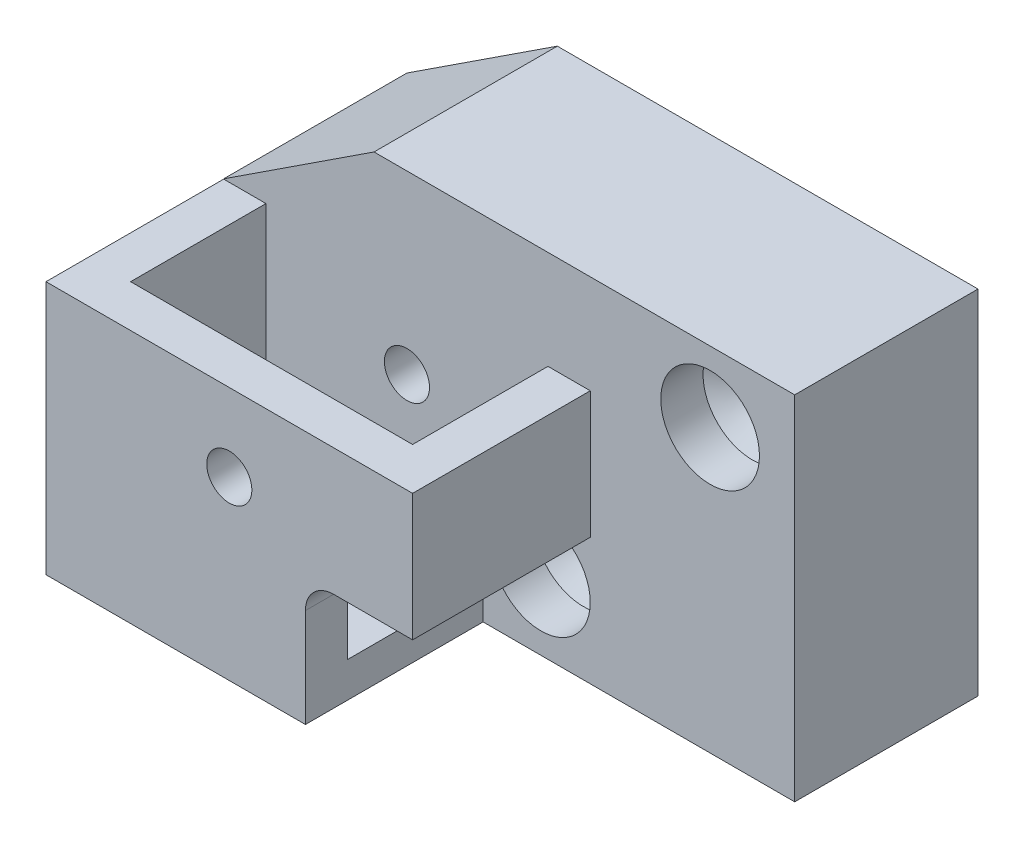
SolidWorks part; units mm, degrees
ref_plane "Спереди" through (0, 0, 0) normal (0, 0, 1) x (1, 0, 0)
ref_plane "Сверху" through (0, 0, 0) normal (0, 1, 0) x (1, 0, 0)
ref_plane "Справа" through (0, 0, 0) normal (1, 0, 0) x (0, 0, -1)
ref_plane "Плоскость4" through (272.1, 0, 0) normal (1, 0, 0) x (0, 0, -1)
sketch "Эскиз1" plane through (272.1, 0, 0) normal (1, 0, 0) x (0, 0, -1)
  line L0 (-23.1, 24) -> (-23.1, 15)
  line L1 (-23.1, 15) -> (-10.5, 15)
  line L2 (-10.5, 15) -> (-10.5, 24)
  line L3 (-10.5, 24) -> (-23.1, 24)
extrude "Бобышка-Вытянуть1" add sketch "Эскиз1" against normal blind 3
sketch "Эскиз2" plane through (269.1, 0, 0) normal (-1, 0, 0) x (0, 0, 1)
  line L0 (20.1, 15) -> (20.1, 24)
  line L1 (20.1, 24) -> (23.1, 24)
  line L2 (23.1, 24) -> (23.1, 15)
  line L3 (23.1, 15) -> (20.1, 15)
extrude "Бобышка-Вытянуть2" add sketch "Эскиз2" along normal blind 20
sketch "Эскиз3" plane through (249.1, 0, 0) normal (-1, 0, 0) x (0, 0, 1)
  line L0 (23.1, 15) -> (10.5, 15)
  line L1 (10.5, 15) -> (10.5, 24)
  line L2 (10.5, 24) -> (23.1, 24)
  line L3 (23.1, 24) -> (23.1, 15)
extrude "Бобышка-Вытянуть3" add sketch "Эскиз3" along normal blind 3
sketch "Эскиз4" plane through (0, 15, 0) normal (0, -1, 0) x (1, 0, 0)
  line L0 (264.5, 23.1) -> (264.5, 20.1)
  line L1 (264.5, 20.1) -> (249.1, 20.1)
  line L2 (249.1, 20.1) -> (249.1, 10.5)
  line L3 (249.1, 10.5) -> (246.1, 10.5)
  line L4 (246.1, 10.5) -> (246.1, 23.1)
  line L5 (246.1, 23.1) -> (264.5, 23.1)
extrude "Бобышка-Вытянуть4" add sketch "Эскиз4" along normal blind 6.5
sketch "Эскиз5" plane through (0, 8.5, 0) normal (0, -1, 0) x (1, 0, 0)
  line L0 (246.1, 10.5) -> (246.1, 23.1)
  line L1 (246.1, 23.1) -> (264.5, 23.1)
  line L2 (264.5, 23.1) -> (264.5, 10.5)
  line L3 (264.5, 10.5) -> (246.1, 10.5)
extrude "Бобышка-Вытянуть5" add sketch "Эскиз5" along normal blind 2.5
sketch "Эскиз6" plane through (0, 0, 10.5) normal (0, 0, -1) x (-1, 0, 0)
  line L0 (-246.1, 31) -> (-246.1, 6)
  line L1 (-246.1, 6) -> (-286.6, 6)
  line L2 (-286.6, 6) -> (-286.6, 31)
  line L3 (-286.6, 31) -> (-246.1, 31)
extrude "Бобышка-Вытянуть6" add sketch "Эскиз6" along normal blind 13
sketch "Эскиз7" plane through (0, 0, -2.5) normal (0, 0, -1) x (-1, 0, 0)
  line L0 (-257.4546, 15.65) -> (-255.8091, 18.5)
  line L1 (-255.8091, 18.5) -> (-257.4546, 21.35)
  line L2 (-257.4546, 21.35) -> (-260.7454, 21.35)
  line L3 (-260.7454, 21.35) -> (-262.3909, 18.5)
  line L4 (-262.3909, 18.5) -> (-260.7454, 15.65)
  line L5 (-260.7454, 15.65) -> (-257.4546, 15.65)
extrude "Вырез-Вытянуть1" cut sketch "Эскиз7" against normal blind 3
hole_wizard "Зенковка для  винта с плоской головкой M31" positions "Эскиз9" profile "Эскиз8" countersink size "M3" standard "Ansi Metric"
sketch "Эскиз9" plane through (0, 0, 10.5) normal (0, 0, 1) x (1, 0, 0)
  point P0 (280.6, 26)
  point P1 (268.6, 11)
sketch "Эскиз8" plane through (280.6, 26, 10.5) normal (1, 0, 0) x (0, -1, 0)
  line L0 (0, 0) -> (0, 13)
  line L1 (0, 13) -> (1.6, 13)
  line L2 (1.6, 13) -> (1.6, 4.1416)
  line L3 (1.6, 4.1416) -> (3.5, 3)
  line L4 (3.5, 3) -> (3.5, 0)
  line L6 (3.5, 0) -> (0, 0)
  line L7 (-1.6, 4.1416) -> (-3.5, 3) construction
  line L11 (0, -6.35) -> (0, 107.95) construction
  dimension "Диаметр сквозного отверстия" = 3.2
  dimension "Глубина сквозного отверстия" = 13
  dimension "Диаметр зенковки" = 7
  dimension "Угол зенковки" = 118
  dimension "Утопленность" = 3
hole_wizard "Диаметр отверстия Ø3.2 (3.2)1" positions "Эскиз11" profile "Эскиз10" hole size "Ø3.2" standard "Ansi Metric"
sketch "Эскиз11" plane through (0, 0, 10.5) normal (0, 0, 1) x (1, 0, 0)
  point P0 (259.1, 18.5)
sketch "Эскиз10" plane through (259.1, 18.5, 10.5) normal (1, 0, 0) x (0, -1, 0)
  line L0 (0, 0) -> (0, 13)
  line L1 (0, 13) -> (1.6, 13)
  line L2 (1.6, 13) -> (1.6, 0)
  line L5 (1.6, 0) -> (0, 0)
  line L11 (0, -6.35) -> (0, 107.95) construction
  dimension "Диаметр сквозного отверстия" = 3.2
  dimension "Глубина сквозного отверстия" = 13
hole_wizard "Диаметр отверстия Ø3.2 (3.2)2" positions "Эскиз13" profile "Эскиз12" hole size "Ø3.2" standard "Ansi Metric"
sketch "Эскиз13" plane through (0, 0, 23.1) normal (0, 0, 1) x (1, 0, 0)
  point P0 (259.1, 18.5)
sketch "Эскиз12" plane through (259.1, 18.5, 23.1) normal (1, 0, 0) x (0, -1, 0)
  line L0 (0, 0) -> (0, 25.6)
  line L1 (0, 25.6) -> (1.6, 25.6)
  line L2 (1.6, 25.6) -> (1.6, 0)
  line L5 (1.6, 0) -> (0, 0)
  line L11 (0, -6.35) -> (0, 107.95) construction
  dimension "Диаметр сквозного отверстия" = 3.2
  dimension "Глубина сквозного отверстия" = 25.6
chamfer "Фаска1" distance 6.982 angle 56.789 1 edges at (246.1, 31, 4)
fillet "Скругление1" radius 2 2 edges at (249.1, 8.5, 15.3) (264.5, 15, 21.6)
